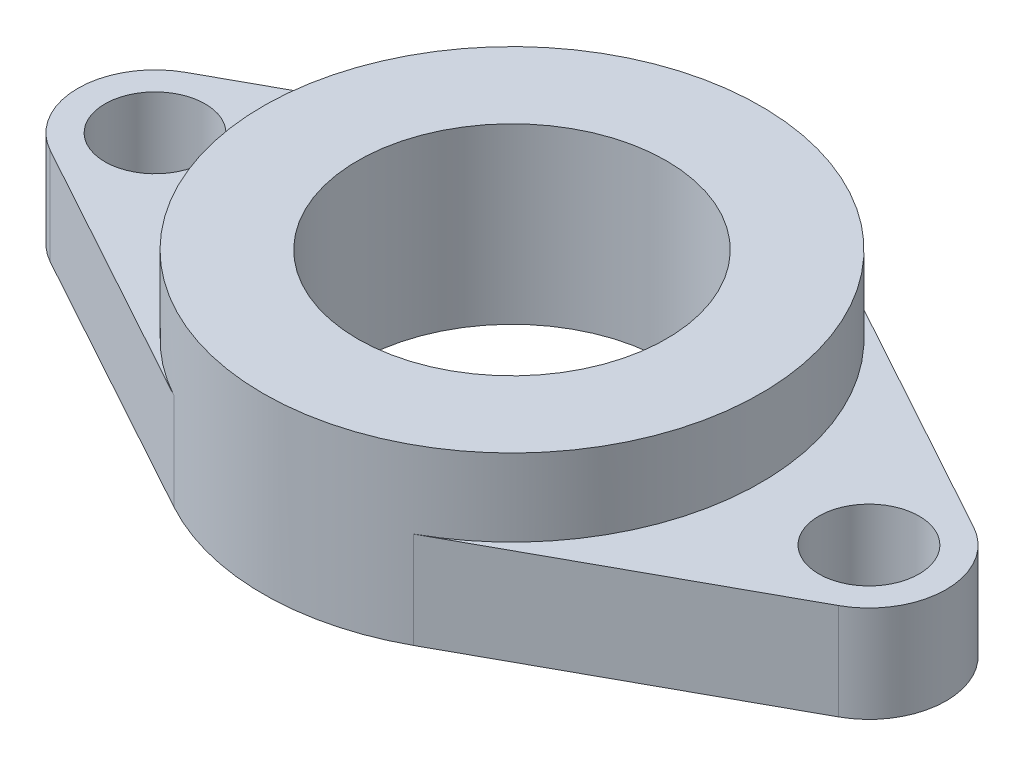
SolidWorks part; units mm, degrees
ref_plane "前视基准面" through (0, 0, 0) normal (0, 0, 1) x (1, 0, 0)
ref_plane "上视基准面" through (0, 0, 0) normal (0, 1, 0) x (1, 0, 0)
ref_plane "右视基准面" through (0, 0, 0) normal (1, 0, 0) x (0, 0, -1)
sketch "草图3" plane through (0, 0, 0) normal (0, 1, 0) x (1, 0, 0)
  circle A0 centre (0, 0) radius 12.9
  dimension "D1" = 25.8
extrude "凸台-拉伸1" add sketch "草图3" along normal blind 9
sketch "草图4" plane through (0, 0, 0) normal (0, 1, 0) x (1, 0, 0)
  line L0 (0, 0) -> (0, 27.1564) construction
  line L1 (-20.4243, 3.5067) -> (-6.2059, 11.3091)
  line L2 (-20.4243, -3.5067) -> (-6.2059, -11.3091)
  line L3 (6.2059, 11.3091) -> (20.4243, 3.5067)
  line L4 (6.2059, -11.3091) -> (20.4243, -3.5067)
  arc A0 (-20.4243, 3.5067) -> (-20.4243, -3.5067) centre (-18.5, 0) ccw
  arc A1 (20.4243, -3.5067) -> (20.4243, 3.5067) centre (18.5, 0) ccw
  circle A2 centre (0, 0) radius 12.9 construction
  arc A3 (-6.2059, -11.3091) -> (6.2059, -11.3091) centre (0, 0) ccw
  arc A4 (6.2059, 11.3091) -> (-6.2059, 11.3091) centre (0, 0) ccw
  dimension "D1" = 8
  dimension "D2" = 8
  dimension "D3" = 37
extrude "凸台-拉伸2" add sketch "草图4" along normal blind 5
sketch "草图5" plane through (0, 9, 0) normal (0, 1, 0) x (1, 0, 0)
  circle A0 centre (0, 0) radius 6.1
  dimension "D1" = 12.2
extrude "凸台-拉伸3" add sketch "草图5" along normal blind 2.5
sketch "草图6" plane through (0, 11.5, 0) normal (0, 1, 0) x (1, 0, 0)
  circle A0 centre (0, 0) radius 4
  dimension "D1" = 8
extrude "切除-拉伸1" cut sketch "草图6" against normal through all
sketch "草图7" plane through (0, 5, 0) normal (0, 1, 0) x (1, 0, 0)
  circle A0 centre (18.5, 0) radius 2.6
  circle A1 centre (-18.5, 0) radius 2.6
  dimension "D1" = 5.2
  dimension "D2" = 5.2
extrude "切除-拉伸2" cut sketch "草图7" against normal through all
sketch "草图8" plane through (0, 9, 0) normal (0, 1, 0) x (1, 0, 0)
  circle A0 centre (0, 0) radius 8
  dimension "D1" = 16
extrude "切除-拉伸3" cut sketch "草图8" against normal blind 15 and the other way blind 17
sketch "草图9" plane through (0, 0, 0) normal (0, -1, 0) x (1, 0, 0)
  line L0 (-18.5, 0) -> (18.5, 0) construction
